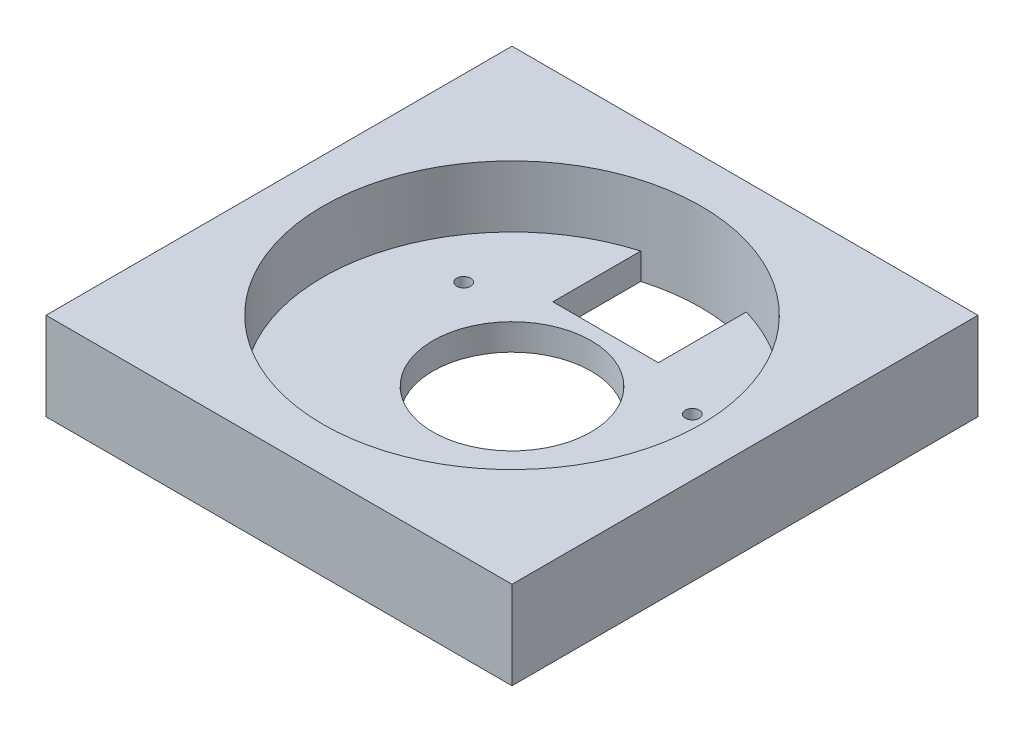
SolidWorks part; units mm, degrees
ref_plane "前视基准面" through (0, 0, 0) normal (0, 0, 1) x (1, 0, 0)
ref_plane "上视基准面" through (0, 0, 0) normal (0, 1, 0) x (1, 0, 0)
ref_plane "右视基准面" through (0, 0, 0) normal (1, 0, 0) x (0, 0, -1)
sketch "草图1" plane through (0, 0, 0) normal (0, 1, 0) x (1, 0, 0)
  line L4 (-26.5, 26.5) -> (26.5, 26.5)
  line L5 (-26.5, 26.5) -> (-26.5, -26.5)
  line L6 (-26.5, -26.5) -> (26.5, -26.5)
  line L7 (26.5, 26.5) -> (26.5, -26.5)
  line L8 (0, -26.5) -> (0, 26.5) construction
  line L9 (-26.5, 0) -> (26.5, 0) construction
  circle A0 centre (0, 0) radius 21.5
  dimension "D1" = 26.5
  dimension "D2" = 43
  dimension "D3" = 26.5
extrude "凸台-拉伸1" add sketch "草图1" along normal blind 7
sketch "草图2" plane through (0, 0, 0) normal (0, -1, 0) x (1, 0, 0)
  line L0 (-6, -20.6458) -> (-6, -10.6458)
  line L1 (-26.5, 26.5) -> (26.5, 26.5)
  line L2 (-26.5, 26.5) -> (-26.5, -26.5)
  line L3 (-26.5, -26.5) -> (26.5, -26.5)
  line L4 (26.5, 26.5) -> (26.5, -26.5)
  line L5 (0, -26.5) -> (0, 26.5) construction
  line L6 (-26.5, 0) -> (26.5, 0) construction
  line L7 (13, -7.5056) -> (0, 15.0111) construction
  line L8 (0, 15.0111) -> (-13, -7.5056) construction
  line L9 (-13, -7.5056) -> (13, -7.5056) construction
  line L10 (-6, -10.6458) -> (6, -10.6458) construction
  line L11 (-6, -10.6458) -> (-6, -20.6458) construction
  line L12 (-6, -20.6458) -> (6, -20.6458) construction
  line L13 (6, -10.6458) -> (6, -20.6458) construction
  line L14 (0, -20.6458) -> (0, -10.6458) construction
  line L15 (-6, -15.6458) -> (6, -15.6458) construction
  line L16 (-6, -10.6458) -> (6, -10.6458)
  line L17 (6, -10.6458) -> (6, -20.6458)
  circle A0 centre (0, 0) radius 7.5056 construction
  circle A1 centre (-13, -7.5056) radius 0.8
  circle A2 centre (0, 15.0111) radius 0.8
  circle A3 centre (13, -7.5056) radius 0.8
  circle A4 centre (0, 0) radius 9
  circle A5 centre (0, 0) radius 21.5 construction
  arc A6 (-6, -20.6458) -> (6, -20.6458) centre (0, 0) ccw
  point P12 (0, -15.6458)
  point P152 (0, 0)
  dimension "D2" = 1.6
  dimension "D4" = 18
  dimension "D6" = 43
  dimension "D1" = 26
  dimension "D5" = 10
  dimension "D7" = 12
  dimension "D3" = 3
extrude "凸台-拉伸2" add sketch "草图2" along normal blind 3
